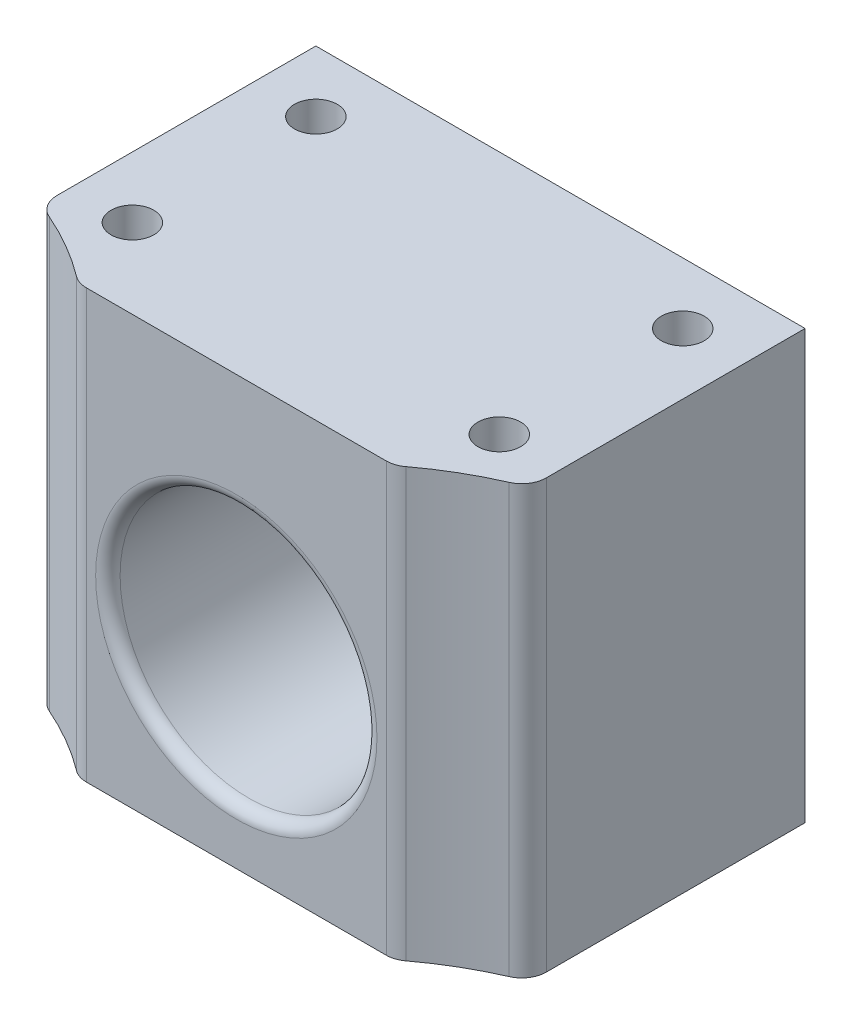
SolidWorks part; units mm, degrees
material "ABS"
ref_plane "前视基准面" through (0, 0, 0) normal (0, 0, 1) x (1, 0, 0)
ref_plane "上视基准面" through (0, 0, 0) normal (0, 1, 0) x (1, 0, 0)
ref_plane "右视基准面" through (0, 0, 0) normal (1, 0, 0) x (0, 0, -1)
sketch "草图1" plane through (0, 0, 0) normal (0, 1, 0) x (1, 0, 0)
  line L0 (-20, 13.2525) -> (-20, -7.9092)
  line L1 (-20, 13.2525) -> (20, 13.2525)
  line L2 (20, 13.2525) -> (20, -7.9092)
  line L3 (12.2609, -13.2525) -> (-12.2609, -13.2525)
  arc A0 (-18.8003, -9.7421) -> (-13.4605, -12.8527) centre (-29.5, -34.2475) cw
  arc A1 (18.8003, -9.7421) -> (13.4605, -12.8527) centre (29.5, -34.2475) ccw
  arc A2 (18.8003, -9.7421) -> (20, -7.9092) centre (18, -7.9092) ccw
  arc A3 (13.4605, -12.8527) -> (12.2609, -13.2525) centre (12.2609, -11.2525) cw
  arc A4 (-12.2609, -13.2525) -> (-13.4605, -12.8527) centre (-12.2609, -11.2525) cw
  arc A5 (-18.8003, -9.7421) -> (-20, -7.9092) centre (-18, -7.9092) cw
  dimension "D1" = 2
extrude "高35mm" add sketch "草图1" along normal blind 35
sketch "草图2" plane through (0, 0, -13.2525) normal (0, 0, -1) x (-1, 0, 0)
  circle A0 centre (0, 15) radius 10.5
  dimension "D1" = 21
  dimension "D2" = 15
extrude "切除-拉伸1" cut sketch "草图2" against normal up to next
fillet "圆角1" radius 1 2 edges at (-10.5, 15, -13.2525) (-10.5, 15, 13.2525)
sketch "草图3" plane through (0, 35, 0) normal (0, 1, 0) x (1, 0, 0)
  line L0 (20, 13.2525) -> (-20, 13.2525) construction
  line L1 (-20, 13.2525) -> (-20, -7.9092) construction
  circle A0 centre (-15, 8.2525) radius 1.75
  circle A1 centre (-15, -6.7475) radius 1.75
  circle A2 centre (15, -6.7475) radius 1.75
  circle A3 centre (15, 8.2525) radius 1.75
  dimension "D4" = 3.5
  dimension "D5" = 3.5
  dimension "D6" = 3.5
  dimension "D7" = 3.5
  dimension "D1" = 5
  dimension "D2" = 5
  dimension "D3" = 15
extrude "φ3.1通孔" cut sketch "草图3" against normal blind 35
